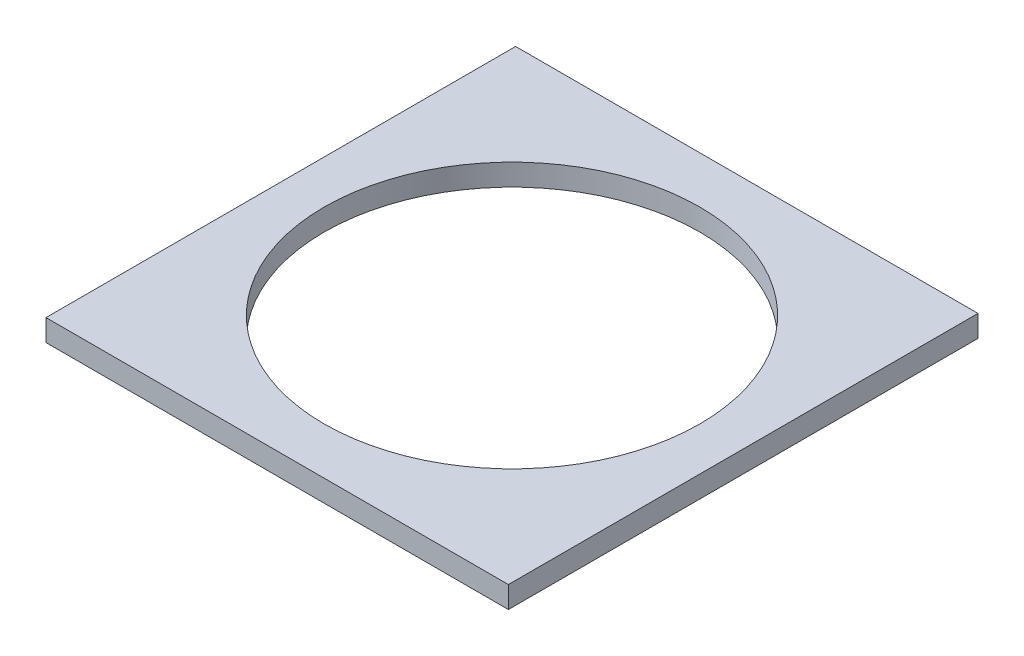
SolidWorks part; units mm, degrees
ref_plane "Front Plane" through (0, 0, 0) normal (0, 0, 1) x (1, 0, 0)
ref_plane "Top Plane" through (0, 0, 0) normal (0, 1, 0) x (1, 0, 0)
ref_plane "Right Plane" through (0, 0, 0) normal (1, 0, 0) x (0, 0, -1)
sketch "Sketch2" plane through (0, 0, 0) normal (0, 1, 0) x (1, 0, 0)
  line L0 (32, -32.5) -> (32, 32.5)
  line L1 (-32, -32.5) -> (32, -32.5)
  line L2 (-32, 32.5) -> (-32, -32.5)
  line L3 (32, 32.5) -> (-32, 32.5)
  circle A0 centre (0, 0) radius 26
  point P6 (0, 0)
  dimension "D3" = 52
  dimension "D1" = 65
  dimension "D2" = 64
  dimension "D4" = 32
  dimension "D5" = 32.5
extrude "Boss-Extrude1" add sketch "Sketch2" along normal blind 3
